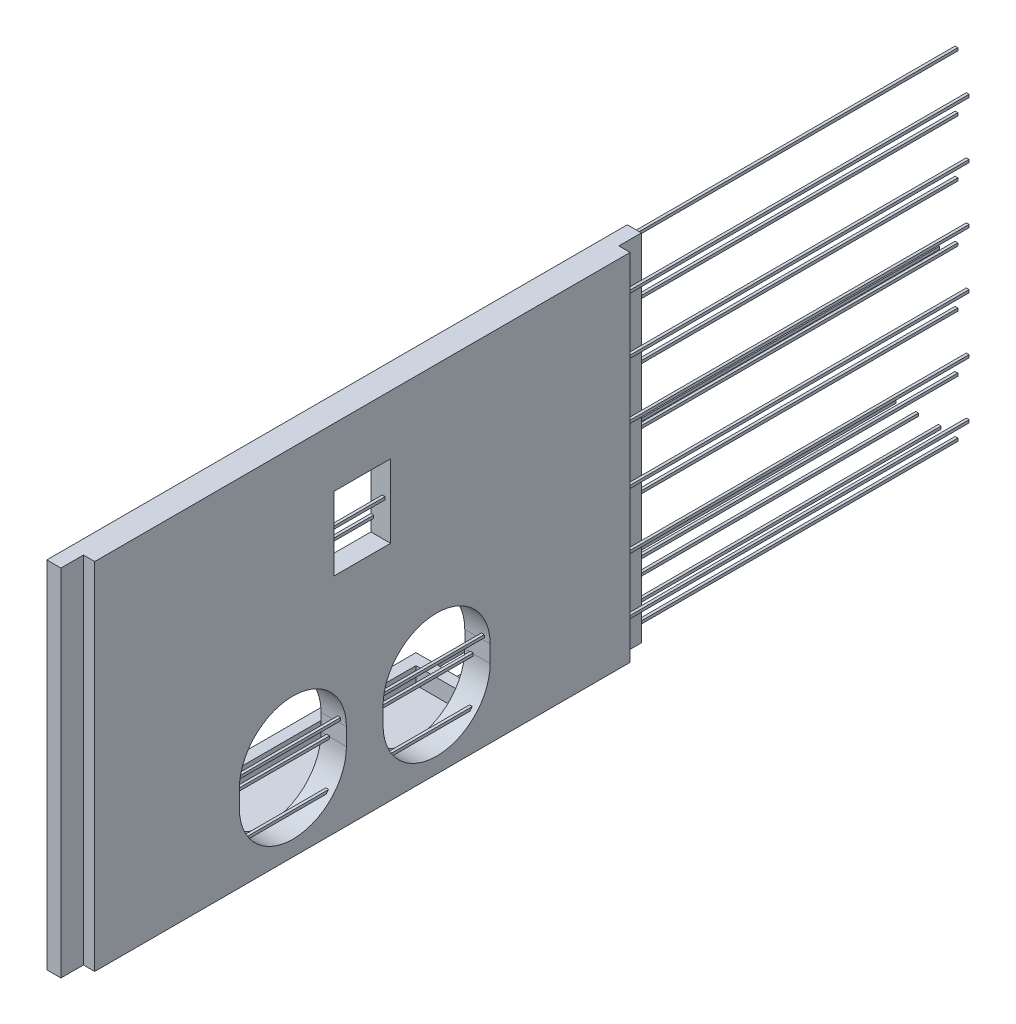
SolidWorks part; units mm, degrees
ref_plane "정면" through (0, 0, 0) normal (0, 0, 1) x (1, 0, 0)
ref_plane "윗면" through (0, 0, 0) normal (0, 1, 0) x (1, 0, 0)
ref_plane "우측면" through (0, 0, 0) normal (1, 0, 0) x (0, 0, -1)
sketch "스케치1" plane through (0, 0, 0) normal (0, 1, 0) x (1, 0, 0)
  line L0 (-2.25, 51.5) -> (0.25, 51.5)
  line L1 (-2.25, 51.5) -> (-2.25, -51.5)
  line L2 (-2.25, -51.5) -> (0.25, -51.5)
  line L3 (0.25, 51.5) -> (0.25, -51.5)
  line L4 (0.25, 47.5) -> (2.25, 47.5)
  line L5 (0.25, 47.5) -> (0.25, -47.5)
  line L6 (0.25, -47.5) -> (2.25, -47.5)
  line L7 (2.25, 47.5) -> (2.25, -47.5)
  dimension "D1" = 2.5
  dimension "D2" = 4
extrude "보스-돌출1" add sketch "스케치1" along normal blind 63 contours L3 L0 L1 L2 | L7 L4 L3 L6
sketch "스케치2" plane through (-2.25, 0, 0) normal (-1, 0, 0) x (0, 0, 1)
  line L0 (-51.5, 0) -> (51.5, 0) construction
  line L1 (-22.5, 22.5) -> (22.5, 22.5)
  line L2 (-22.5, 22.5) -> (-22.5, 2)
  line L3 (-22.5, 2) -> (22.5, 2)
  line L4 (22.5, 22.5) -> (22.5, 2)
  line L5 (51.5, 63) -> (51.5, 0) construction
  dimension "D1" = 45
  dimension "D2" = 20.5
  dimension "D3" = 2
  dimension "D4" = 29
sketch "스케치5" plane through (-2.25, 0, 0) normal (-1, 0, 0) x (0, 0, 1)
  line L1 (-25, 2) -> (25, 2)
  line L2 (-25, 2) -> (-25, 0)
  line L3 (-25, 0) -> (25, 0)
  line L4 (25, 2) -> (25, 0)
  line L5 (-51.5, 63) -> (-51.5, 0) construction
  dimension "D1" = 26.5
  dimension "D2" = 50
extrude "보스-돌출2" add sketch "스케치5" along normal blind 11
sketch "스케치7" plane through (0, 2, 0) normal (0, 1, 0) x (1, 0, 0)
  line L0 (-2.25, 23) -> (-11.25, 23)
  line L1 (-11.25, 23) -> (-11.25, -23)
  line L2 (-11.25, -23) -> (-2.25, -23)
  line L3 (-2.25, 23) -> (-2.25, 25)
  line L4 (-2.25, -25) -> (-2.25, 25)
  line L5 (-2.25, 25) -> (-13.25, 25)
  line L6 (-13.25, 25) -> (-13.25, -25)
  line L7 (-13.25, -25) -> (-2.25, -25)
  line L8 (-2.25, -25) -> (-2.25, -23)
  line L9 (-2.25, 25) -> (-13.25, 25)
  line L10 (-13.25, 25) -> (-13.25, -25)
  line L11 (-13.25, -25) -> (-2.25, -25)
  dimension "D1" = 0
  dimension "D2" = 2
extrude "보스-돌출3" add sketch "스케치7" along normal blind 3
sketch "스케치9" plane through (0, 2, 0) normal (0, 1, 0) x (1, 0, 0)
  line L0 (-11.25, -23) -> (-11.25, 23) construction
  line L1 (-10.75, 22.5) -> (-9, 22.5)
  line L2 (-10.75, 22.5) -> (-10.75, -22.5)
  line L3 (-10.75, -22.5) -> (-9, -22.5)
  line L4 (-9, 22.5) -> (-9, -22.5)
  line L5 (-2.25, -23) -> (-11.25, -23) construction
  dimension "D1" = 45
  dimension "D2" = 1.75
  dimension "D3" = 0.5
  dimension "D4" = 0.5
sketch "스케치10" plane through (2.25, 0, 0) normal (1, 0, 0) x (0, 0, -1)
  line L0 (-12.34, 12.25) -> (-12.34, 15.25) construction
  line L1 (13.16, 12.25) -> (13.16, 15.25) construction
  line L2 (-21.84, 15.25) -> (-21.84, 12.25)
  line L3 (-2.84, 15.25) -> (-2.84, 12.25)
  line L4 (3.66, 15.25) -> (3.66, 12.25)
  line L5 (22.66, 15.25) -> (22.66, 12.25)
  arc A0 (-21.84, 12.25) -> (-2.84, 12.25) centre (-12.34, 12.25) ccw
  arc A1 (3.66, 12.25) -> (22.66, 12.25) centre (13.16, 12.25) ccw
  arc A2 (-2.84, 15.25) -> (-21.84, 15.25) centre (-12.34, 15.25) ccw
  arc A3 (22.66, 15.25) -> (3.66, 15.25) centre (13.16, 15.25) ccw
  dimension "D1" = 19
  dimension "D2" = 19
  dimension "D4" = 19
  dimension "D5" = 19
  dimension "D3" = 3
extrude "컷-돌출1" cut sketch "스케치10" against normal up to surface (4.5 mm away) up to face at (-2.25, 12.5, 0)
sketch "스케치11" plane through (-2.25, 0, 0) normal (-1, 0, 0) x (0, 0, 1)
  line L0 (-51.5, 63) -> (-51.5, 0) construction
  line L1 (-12.5, 57) -> (12.5, 57)
  line L2 (-12.5, 57) -> (-12.5, 30)
  line L3 (-12.5, 30) -> (12.5, 30)
  line L4 (12.5, 57) -> (12.5, 30)
  line L7 (-4.25, 51.8) -> (4.25, 51.8)
  line L8 (-4.25, 51.8) -> (-4.25, 40.3)
  line L9 (-4.25, 40.3) -> (4.25, 40.3)
  line L10 (4.25, 51.8) -> (4.25, 40.3)
  dimension "D1" = 25
  dimension "D2" = 27
  dimension "D3" = 39
  dimension "D5" = 8.25
  dimension "D7" = 11.5
  dimension "D8" = 8.5
extrude "컷-돌출2" cut sketch "스케치11" against normal up to surface (4.5 mm away) contours L10 L7 L8 L9 up to face at (2.25, 13.75, 12.34)
sketch "스케치12" plane through (-2.25, 0, 0) normal (-1, 0, 0) x (0, 0, 1)
  line L0 (-13, 57.5) -> (-13, 29.5)
  line L1 (-12.5, 57) -> (12.5, 57)
  line L2 (-12.5, 57) -> (-12.5, 30)
  line L3 (-12.5, 30) -> (12.5, 30)
  line L4 (12.5, 57) -> (12.5, 30)
  line L5 (-13, 29.5) -> (13, 29.5)
  line L6 (13, 57.5) -> (13, 29.5)
  line L7 (-13, 57.5) -> (13, 57.5)
  line M21 (4.25, 51.8) -> (4.25, 40.3)
  line M22 (4.25, 40.3) -> (-4.25, 40.3)
  line M23 (-4.25, 40.3) -> (-4.25, 51.8)
  line M24 (-4.25, 51.8) -> (4.25, 51.8)
  dimension "D1" = 0.5
extrude "컷-돌출3" cut sketch "스케치12" against normal blind 1 contours L4 L1 L2 L3 M24 M21 M22 M23 | L7 L0 L5 L6 L1 L4 L3 L2
sketch "스케치13" plane through (-2.25, 0, 0) normal (-1, 0, 0) x (0, 0, 1)
  line L0 (-51.5, 63) -> (-51.5, 0) construction
  line L1 (-15, 29.5) -> (15, 29.5)
  line L2 (-15, 29.5) -> (-15, 27.5)
  line L3 (-15, 27.5) -> (15, 27.5)
  line L4 (15, 29.5) -> (15, 27.5)
  line L6 (-13, 29.5) -> (13, 29.5) construction
  dimension "D1" = 36.5
  dimension "D2" = 30
  dimension "D3" = 2
extrude "보스-돌출4" add sketch "스케치13" along normal blind 4
sketch "스케치14" plane through (0, 29.5, 0) normal (0, 1, 0) x (1, 0, 0)
  line L0 (-2.25, -13) -> (-2.25, -15)
  line L1 (-6.25, 15) -> (-2.25, 15)
  line L2 (-6.25, 15) -> (-6.25, -15)
  line L3 (-6.25, -15) -> (-2.25, -15)
  line L4 (-2.25, 15) -> (-2.25, 13)
  line L5 (-4.25, 13) -> (-2.25, 13)
  line L6 (-4.25, 13) -> (-4.25, -13)
  line L7 (-4.25, -13) -> (-2.25, -13)
  dimension "D1" = 2
  dimension "D2" = 2
  dimension "D3" = 2
  dimension "D4" = 2
extrude "보스-돌출5" add sketch "스케치14" along normal blind 3
sketch "스케치15" plane through (2.25, 0, 0) normal (1, 0, 0) x (0, 0, -1)
  line L0 (5, 39.55) -> (5, 52.55)
  line L1 (4.25, 40.3) -> (-4.25, 40.3)
  line L2 (4.25, 40.3) -> (4.25, 51.8)
  line L3 (4.25, 51.8) -> (-4.25, 51.8)
  line L4 (-4.25, 40.3) -> (-4.25, 51.8)
  line L5 (5, 52.55) -> (-5, 52.55)
  line L6 (-5, 39.55) -> (-5, 52.55)
  line L7 (5, 39.55) -> (-5, 39.55)
  dimension "D1" = 0.75
extrude "컷-돌출5" cut sketch "스케치15" against normal blind 10 contours L2 L3 L4 L1
sketch "스케치16" plane through (0, 0, -51.5) normal (0, 0, -1) x (-1, 0, 0)
  line L1 (0.75, 1.8883) -> (1.25, 1.8883)
  line L2 (0.75, 1.8883) -> (0.75, 2.3883)
  line L3 (0.75, 2.3883) -> (1.25, 2.3883)
  line L4 (1.25, 1.8883) -> (1.25, 2.3883)
  line L5 (2.25, 63) -> (2.25, 0) construction
  line L6 (0.75, 11.8883) -> (1.25, 11.8883)
  line L7 (0.75, 11.8883) -> (0.75, 12.3883)
  line L8 (0.75, 12.3883) -> (1.25, 12.3883)
  line L9 (1.25, 11.8883) -> (1.25, 12.3883)
  line L10 (0.75, 21.8883) -> (1.25, 21.8883)
  line L11 (0.75, 21.8883) -> (0.75, 22.3883)
  line L12 (0.75, 22.3883) -> (1.25, 22.3883)
  line L13 (1.25, 21.8883) -> (1.25, 22.3883)
  line L14 (0.75, 31.8883) -> (1.25, 31.8883)
  line L15 (0.75, 31.8883) -> (0.75, 32.3883)
  line L16 (0.75, 32.3883) -> (1.25, 32.3883)
  line L17 (1.25, 31.8883) -> (1.25, 32.3883)
  line L18 (0.75, 41.8883) -> (1.25, 41.8883)
  line L19 (0.75, 41.8883) -> (0.75, 42.3883)
  line L20 (0.75, 42.3883) -> (1.25, 42.3883)
  line L21 (1.25, 41.8883) -> (1.25, 42.3883)
  line L22 (0.75, 51.8883) -> (1.25, 51.8883)
  line L23 (0.75, 51.8883) -> (0.75, 52.3883)
  line L24 (0.75, 52.3883) -> (1.25, 52.3883)
  line L25 (1.25, 51.8883) -> (1.25, 52.3883)
  line L26 (0.75, 61.8883) -> (1.25, 61.8883)
  line L27 (0.75, 61.8883) -> (0.75, 62.3883)
  line L28 (0.75, 62.3883) -> (1.25, 62.3883)
  line L29 (1.25, 61.8883) -> (1.25, 62.3883)
  dimension "D1" = 0.5
  dimension "D2" = 0.5
  dimension "D3" = 1
  dimension "D4" = 7
extrude "보스-돌출6" add sketch "스케치16" along normal up to surface and the other way up to surface
sketch "스케치17" plane through (0, 0, -47.5) normal (0, 0, -1) x (-1, 0, 0)
  line L0 (-0.25, 63) -> (-0.25, 0) construction
  line L1 (-1.25, 5.7179) -> (-0.75, 5.7179)
  line L2 (-1.25, 5.7179) -> (-1.25, 6.2179)
  line L3 (-1.25, 6.2179) -> (-0.75, 6.2179)
  line L4 (-0.75, 5.7179) -> (-0.75, 6.2179)
  line L5 (-1.25, 15.7179) -> (-1.25, 16.2179)
  line L6 (-1.25, 15.7179) -> (-0.75, 15.7179)
  line L7 (-0.75, 15.7179) -> (-0.75, 16.2179)
  line L8 (-1.25, 16.2179) -> (-0.75, 16.2179)
  line L9 (-1.25, 25.7179) -> (-1.25, 26.2179)
  line L10 (-1.25, 25.7179) -> (-0.75, 25.7179)
  line L11 (-0.75, 25.7179) -> (-0.75, 26.2179)
  line L12 (-1.25, 26.2179) -> (-0.75, 26.2179)
  line L13 (-1.25, 35.7179) -> (-1.25, 36.2179)
  line L14 (-1.25, 35.7179) -> (-0.75, 35.7179)
  line L15 (-0.75, 35.7179) -> (-0.75, 36.2179)
  line L16 (-1.25, 36.2179) -> (-0.75, 36.2179)
  line L17 (-1.25, 45.7179) -> (-1.25, 46.2179)
  line L18 (-1.25, 45.7179) -> (-0.75, 45.7179)
  line L19 (-0.75, 45.7179) -> (-0.75, 46.2179)
  line L20 (-1.25, 46.2179) -> (-0.75, 46.2179)
  line L21 (-1.25, 55.7179) -> (-1.25, 56.2179)
  line L22 (-1.25, 55.7179) -> (-0.75, 55.7179)
  line L23 (-0.75, 55.7179) -> (-0.75, 56.2179)
  line L24 (-1.25, 56.2179) -> (-0.75, 56.2179)
  dimension "D1" = 0.5
  dimension "D2" = 0.5
  dimension "D3" = 0.5
  dimension "D4" = 6
extrude "보스-돌출7" add sketch "스케치17" along normal up to surface and the other way up to surface
sketch "스케치18" plane through (0, 0, -25) normal (0, 0, -1) x (-1, 0, 0)
  line L1 (3.7268, 2.25) -> (4.2268, 2.25)
  line L2 (3.7268, 2.25) -> (3.7268, 2.75)
  line L3 (3.7268, 2.75) -> (4.2268, 2.75)
  line L4 (4.2268, 2.25) -> (4.2268, 2.75)
  line L5 (13.25, 0) -> (2.25, 0) construction
  line L6 (7.7268, 2.25) -> (7.7268, 2.75)
  line L7 (7.7268, 2.25) -> (8.2268, 2.25)
  line L8 (8.2268, 2.25) -> (8.2268, 2.75)
  line L9 (7.7268, 2.75) -> (8.2268, 2.75)
  line L10 (11.7268, 2.25) -> (11.7268, 2.75)
  line L11 (11.7268, 2.25) -> (12.2268, 2.25)
  line L12 (12.2268, 2.25) -> (12.2268, 2.75)
  line L13 (11.7268, 2.75) -> (12.2268, 2.75)
  dimension "D1" = 0.5
  dimension "D2" = 0.5
  dimension "D3" = 2.25
  dimension "D4" = 3
extrude "보스-돌출8" add sketch "스케치18" along normal up to surface (83.6616 mm away)
sketch "스케치19" plane through (0, 0, -15) normal (0, 0, -1) x (-1, 0, 0)
  line L0 (6.25, 27.5) -> (2.25, 27.5) construction
  line L1 (4, 29.75) -> (4.5, 29.75)
  line L2 (4, 29.75) -> (4, 30.25)
  line L3 (4, 30.25) -> (4.5, 30.25)
  line L4 (4.5, 29.75) -> (4.5, 30.25)
  line L6 (6.25, 32.5) -> (6.25, 27.5) construction
  dimension "D1" = 0.5
  dimension "D2" = 0.5
  dimension "D3" = 2.25
  dimension "D4" = 1.75
extrude "보스-돌출9" add sketch "스케치19" along normal up to surface (93.6616 mm away)
